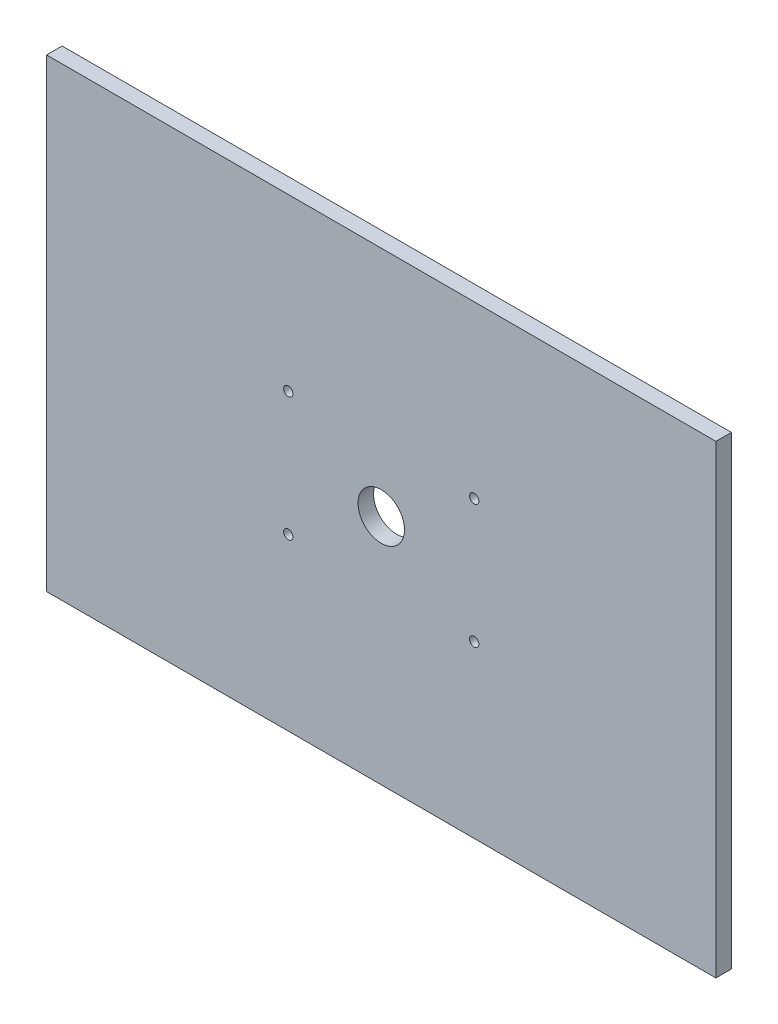
SolidWorks part; units mm, degrees
ref_plane "Front Plane" through (0, 0, 0) normal (0, 0, 1) x (1, 0, 0)
ref_plane "Top Plane" through (0, 0, 0) normal (0, 1, 0) x (1, 0, 0)
ref_plane "Right Plane" through (0, 0, 0) normal (1, 0, 0) x (0, 0, -1)
sketch "Sketch1" plane through (0, 0, 0) normal (0, 0, 1) x (1, 0, 0)
  line L1 (137.16, -95.25) -> (-137.16, -95.25)
  line L2 (137.16, -95.25) -> (137.16, 95.25)
  line L3 (137.16, 95.25) -> (-137.16, 95.25)
  line L4 (-137.16, -95.25) -> (-137.16, 95.25)
  line L5 (137.16, -95.25) -> (-137.16, 95.25) construction
  line L6 (137.16, 95.25) -> (-137.16, -95.25) construction
  point P0 (0, 0)
  dimension "D1" = 190.5
  dimension "D2" = 274.32
extrude "Boss-Extrude1" add sketch "Sketch1" along normal blind 6.35
sketch "Sketch2" plane through (0, 0, 6.35) normal (0, 0, 1) x (1, 0, 0)
  line L1 (-137.16, -95.25) -> (137.16, -95.25) construction
  circle A0 centre (0, 0) radius 9.525
  dimension "D2" = 19.05
extrude "Cut-Extrude1" cut sketch "Sketch2" against normal through all
sketch "Sketch3" plane through (0, 0, 6.35) normal (0, 0, 1) x (1, 0, 0)
  line L0 (-38.1, 25.4) -> (-38.1, -25.4) construction
  line L1 (-38.1, 25.4) -> (38.1, 25.4) construction
  circle A0 centre (-38.1, 25.4) radius 1.905
  circle A1 centre (-38.1, -25.4) radius 1.905
  circle A2 centre (38.1, -25.4) radius 1.905
  circle A3 centre (38.1, 25.4) radius 1.905
  point P8 (-38.1, 0)
  point P9 (0, 25.4)
  dimension "D1" = 3.81
  dimension "D2" = 38.1
  dimension "D3" = 25.4
extrude "Cut-Extrude2" cut sketch "Sketch3" against normal through all
